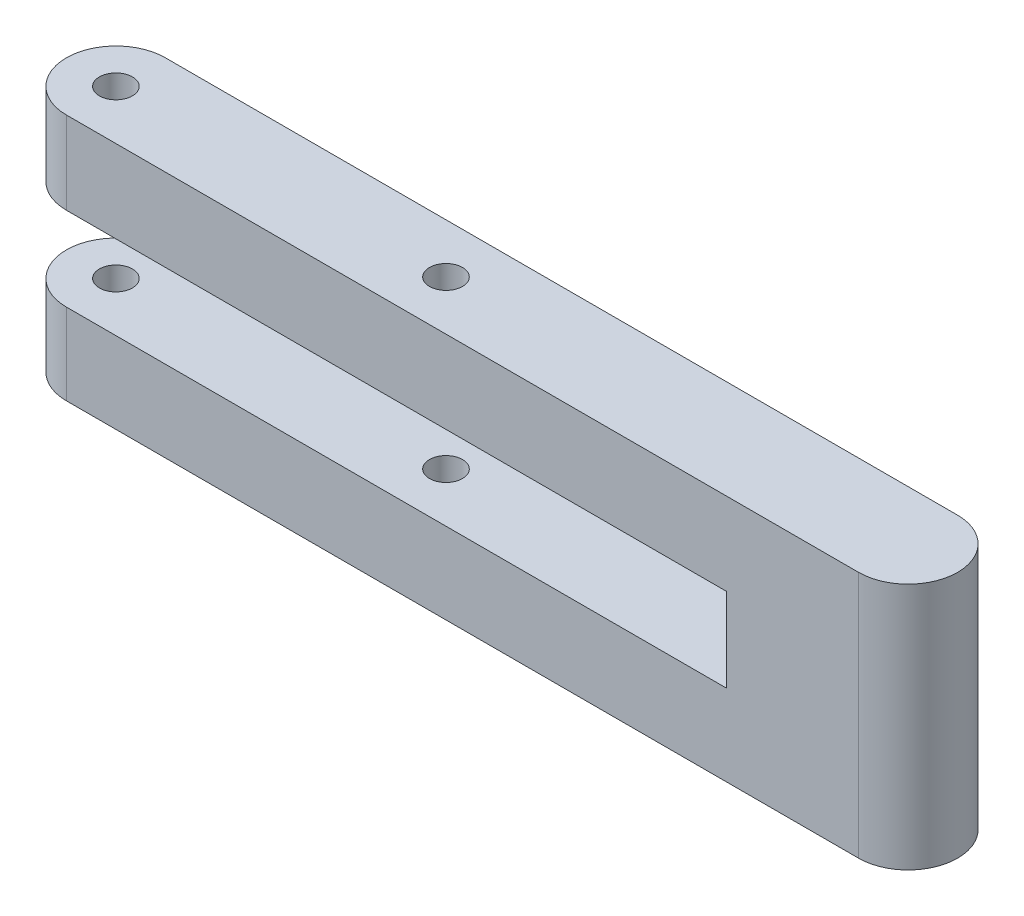
SolidWorks part; units mm, degrees
ref_plane "Front Plane" through (0, 0, 0) normal (0, 0, 1) x (1, 0, 0)
ref_plane "Top Plane" through (0, 0, 0) normal (0, 1, 0) x (1, 0, 0)
ref_plane "Right Plane" through (0, 0, 0) normal (1, 0, 0) x (0, 0, -1)
sketch "Sketch3" plane through (0, 0, 0) normal (0, 1, 0) x (1, 0, 0)
  line L0 (-50.8, 0) -> (71.12, 0) construction
  line L1 (-20.955, 0) -> (20.955, 0) construction
  line L2 (-50.8, 7.62) -> (71.12, 7.62)
  line L3 (-50.8, -7.62) -> (71.12, -7.62)
  arc A0 (-50.8, 7.62) -> (-50.8, -7.62) centre (-50.8, 0) ccw
  arc A1 (71.12, -7.62) -> (71.12, 7.62) centre (71.12, 0) ccw
  point P5 (10.16, 0)
  dimension "D2" = 7.62
  dimension "D1" = 121.92
  dimension "D3" = 50.8
extrude "Boss-Extrude1" add sketch "Sketch3" along normal blind 38.1
sketch "Sketch4" plane through (0, 38.1, 0) normal (0, 1, 0) x (1, 0, 0)
  circle A0 centre (-50.8, 0) radius 2.54
  circle A1 centre (0, 0) radius 2.54
  dimension "D3" = 50.8
  dimension "D1" = 5.08
  dimension "D2" = 2
extrude "Cut-Extrude3" cut sketch "Sketch4" against normal through all
ref_plane "Plane2" through (0, 19.05, 0) normal (0, 1, 0) x (1, 0, 0)
sketch "Sketch5" plane through (0, 19.05, 0) normal (0, 1, 0) x (1, 0, 0)
  line L0 (0, -8.382) -> (0, 8.382) construction
  line L1 (-50.8, 7.62) -> (25.4, 7.62)
  line L2 (-50.8, -7.62) -> (0, -7.62)
  line L3 (-50.8, -7.62) -> (71.12, -7.62) construction
  line L4 (25.4, 7.62) -> (50.8, 7.62)
  line L6 (0, -7.62) -> (50.8, -7.62)
  line L7 (50.8, 7.62) -> (50.8, -7.62)
  arc A0 (-50.8, 7.62) -> (-50.8, -7.62) centre (-50.8, 0) ccw
  point P4 (-7.62, 0)
  point P9 (0, 0)
  dimension "D3" = 50.8
  dimension "D1" = 7.62
  dimension "D2" = 101.6
  dimension "D4" = 15.24
  dimension "D5" = 50.8
  dimension "D6" = 7.62
  dimension "D7" = 7.62
  dimension "D8" = 25.4
extrude "Cut-Extrude4" cut sketch "Sketch5" against normal blind 6.55 and the other way blind 6.35
equation "\"TibiaLength\"= 4in"
equation "\"TibiaRadius\"= 0.3in"
equation "\"TibiaDistFromCentre\"= \"TibiaLength\" / 2"
equation "\"TibiaThickness\"= 0.5in"
equation "\"HoleRadius\"= 0.2in"
equation "\"D1@Sketch3\"= \"TibiaLength\" * 1.2"
equation "\"D2@Sketch3\"= \"TibiaRadius\""
equation "\"D3@Sketch3\"= \"TibiaDistFromCentre\""
equation "\"D1@Boss-Extrude1\"=\"TibiaThickness\"*3"
equation "\"D1@Sketch4\"= \"HoleRadius\""
equation "\"D2@Sketch5\"=\"TibiaLength\""
equation "\"D3@Sketch5\"=\"TibiaDistFromCentre\""
equation "\"D4@Sketch5\"=\"TibiaRadius\"*2"
equation "\"D5@Sketch5\"=\"TibiaDistFromCentre\""
equation "\"D7@Sketch5\"=\"TibiaRadius\""
equation "\"D1@Sketch5\"=\"TibiaRadius\""
equation "\"D6@Sketch5\"=\"TibiaRadius\""
equation "\"D1@Cut-Extrude4\"=\"TibiaThickness\" * 0.5+0.00787402"
equation "\"D2@Cut-Extrude4\"= \"TibiaThickness\" * 0.5"
equation "\"D3@Sketch4\"=\"TibiaLength\"*0.5"
